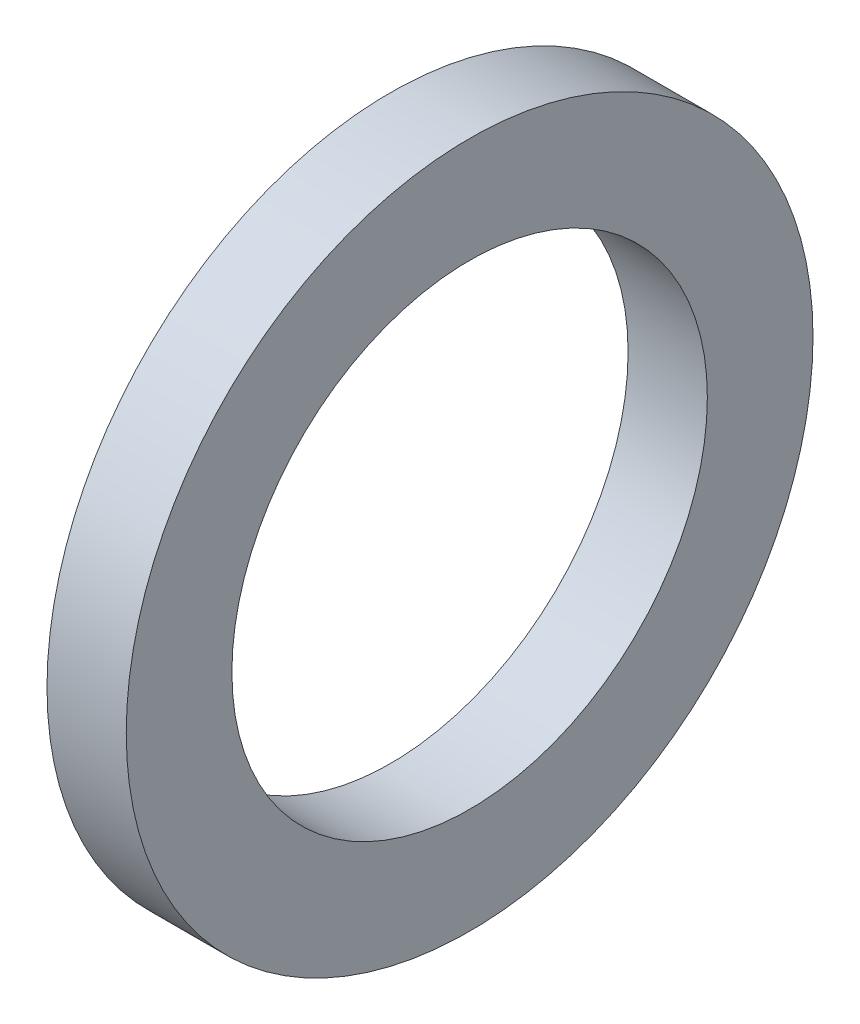
SolidWorks part; units mm, degrees
ref_plane "前视基准面" through (0, 0, 0) normal (0, 0, 1) x (1, 0, 0)
ref_plane "上视基准面" through (0, 0, 0) normal (0, 1, 0) x (1, 0, 0)
ref_plane "右视基准面" through (0, 0, 0) normal (1, 0, 0) x (0, 0, -1)
sketch "草图1" plane through (0, 0, 0) normal (1, 0, 0) x (0, 0, -1)
  circle A0 centre (0, 0) radius 45
  circle A1 centre (0, 0) radius 65
  dimension "D1" = 90
  dimension "D2" = 130
extrude "凸台-拉伸1" add sketch "草图1" along normal blind 15
